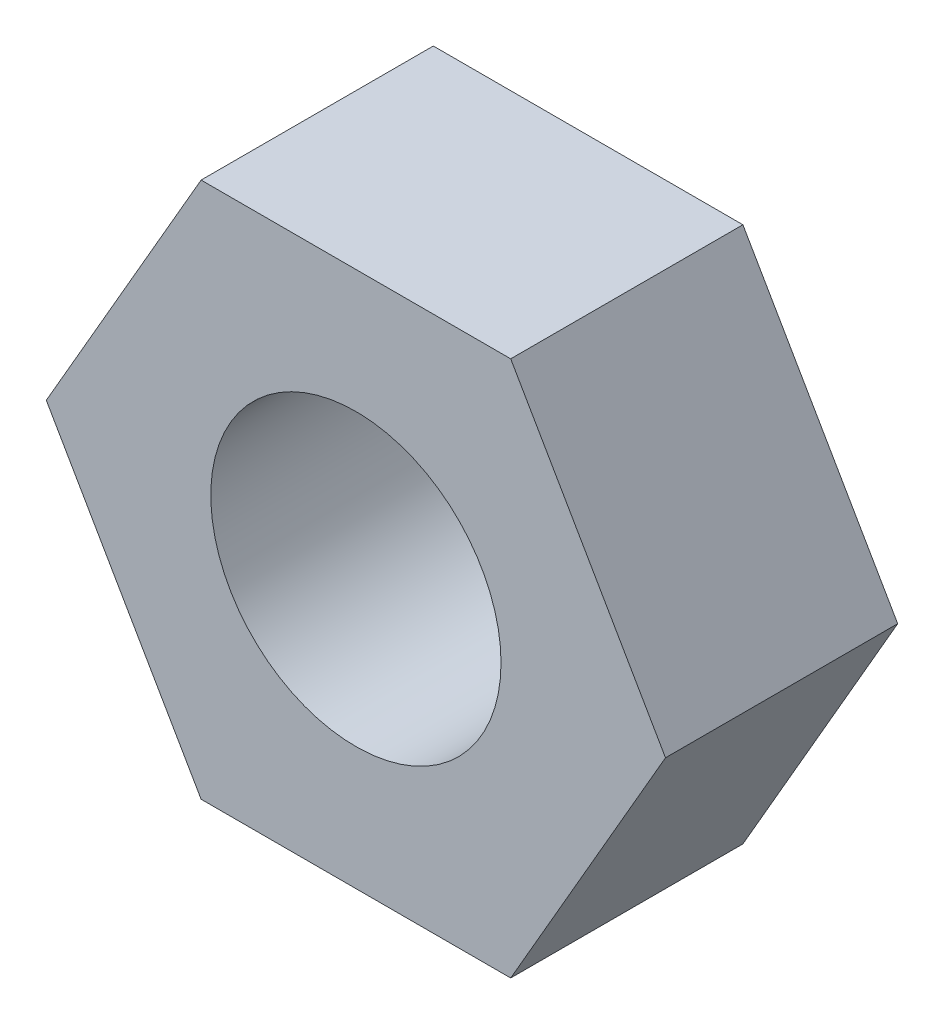
SolidWorks part; units mm, degrees
ref_plane "Plan de face" through (0, 0, 0) normal (0, 0, 1) x (1, 0, 0)
ref_plane "Plan de dessus" through (0, 0, 0) normal (0, 1, 0) x (1, 0, 0)
ref_plane "Plan de droite" through (0, 0, 0) normal (1, 0, 0) x (0, 0, -1)
sketch "Esquisse1" plane through (0, 0, 0) normal (0, 0, 1) x (1, 0, 0)
  line L0 (-3.2, 0) -> (3.2, 0) construction
  line L1 (-1.6, 2.7713) -> (1.6, -2.7713) construction
  line L2 (1.6, 2.7713) -> (-1.6, -2.7713) construction
  line L3 (-1.6, -2.7713) -> (1.6, -2.7713)
  line L4 (1.6, -2.7713) -> (3.2, 0)
  line L5 (3.2, 0) -> (1.6, 2.7713)
  line L6 (1.6, 2.7713) -> (-1.6, 2.7713)
  line L7 (-1.6, 2.7713) -> (-3.2, 0)
  line L8 (-3.2, 0) -> (-1.6, -2.7713)
  circle A0 centre (0, 0) radius 1.5
  circle A1 centre (0, 0) radius 3.2 construction
  dimension "D1" = 3
  dimension "D2" = 6.4
  dimension "D3" = 60
  dimension "D4" = 60
extrude "Extrusion1" add sketch "Esquisse1" along normal blind 2.4
